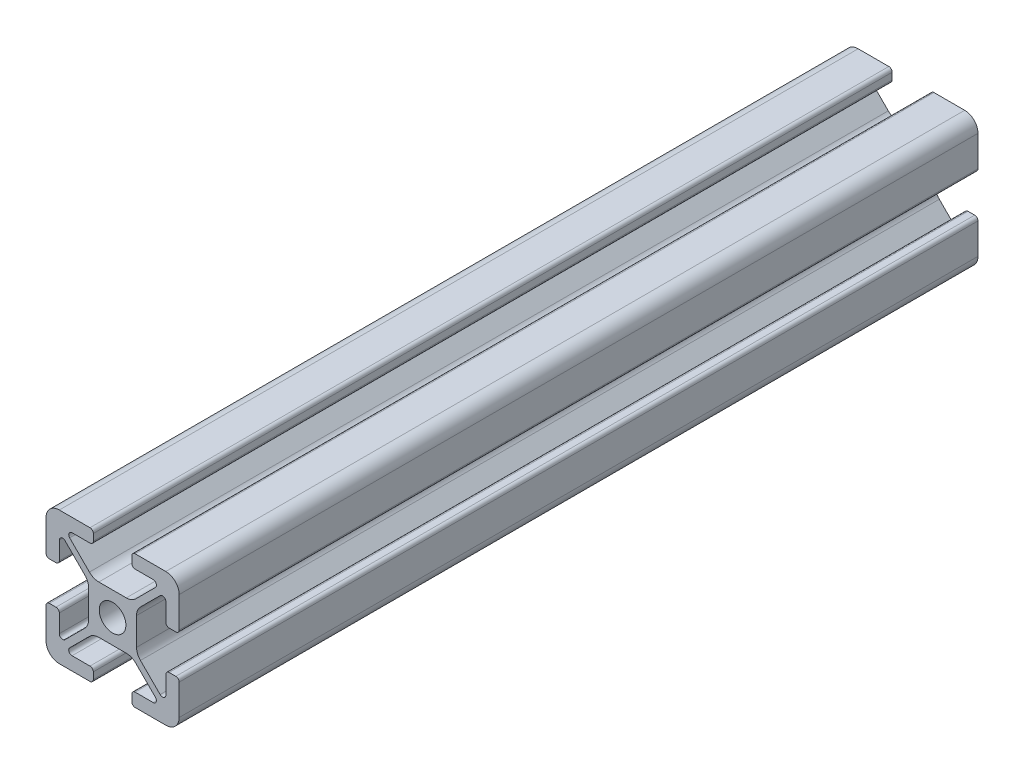
SolidWorks part; units mm, degrees
ref_plane "Front Plane" through (0, 0, 0) normal (0, 0, 1) x (1, 0, 0)
ref_plane "Top Plane" through (0, 0, 0) normal (0, 1, 0) x (1, 0, 0)
ref_plane "Right Plane" through (0, 0, 0) normal (1, 0, 0) x (0, 0, -1)
sketch "Sketch1" plane through (0, 0, 0) normal (0, 0, 1) x (1, 0, 0)
  line L0 (4.4179, 5.3159) -> (8.178, 9.076)
  line L1 (-10.16, -12.7) -> (-4.309, -12.7)
  line L2 (-12.7, -10.16) -> (-12.7, -4.309)
  line L3 (-10.16, 12.7) -> (-4.309, 12.7)
  line L4 (12.7, -10.16) -> (12.7, -4.309)
  line L5 (-12.7, -12.7) -> (12.7, 12.7) construction
  line L6 (-12.7, 12.7) -> (12.7, -12.7) construction
  line L7 (-2.6219, -4.572) -> (2.6219, -4.572)
  line L8 (-4.572, -2.6219) -> (-4.572, 2.6219)
  line L9 (-2.6219, 4.572) -> (2.6219, 4.572)
  line L10 (4.572, -2.6219) -> (4.572, 2.6219)
  line L11 (-4.572, -4.572) -> (4.572, 4.572) construction
  line L12 (-4.572, 4.572) -> (4.572, -4.572) construction
  line L13 (5.3159, 4.4179) -> (9.076, 8.178)
  line L14 (5.3159, -4.4179) -> (9.076, -8.178)
  line L15 (4.4179, -5.3159) -> (8.178, -9.076)
  line L16 (-4.4179, -5.3159) -> (-8.178, -9.076)
  line L17 (-5.3159, -4.4179) -> (-9.076, -8.178)
  line L18 (-5.3159, 4.4179) -> (-9.076, 8.178)
  line L19 (-4.4179, 5.3159) -> (-8.178, 9.076)
  line L20 (-3.674, 4.572) -> (-3.8683, 4.7663) construction
  line L21 (-10.16, 10.16) -> (10.16, 10.16) construction
  line L22 (-7.7289, 10.16) -> (-4.309, 10.16)
  line L23 (10.16, -7.7289) -> (10.16, -4.309)
  line L24 (-7.7289, -10.16) -> (-4.309, -10.16)
  line L25 (-10.16, -7.7289) -> (-10.16, -4.309)
  line L26 (-10.16, -10.16) -> (-10.16, 10.16) construction
  line L27 (-10.16, -10.16) -> (10.16, -10.16) construction
  line L28 (10.16, -10.16) -> (10.16, 10.16) construction
  line L29 (-4.572, 3.674) -> (-17.3082, 3.674) construction
  line L30 (-4.572, -3.674) -> (-17.7261, -3.674) construction
  line L31 (-17.7261, -3.674) -> (20.6347, -3.674) construction
  line L32 (-4.572, 3.674) -> (19.3811, 3.674) construction
  line L33 (-12.7, 4.309) -> (-12.7, 10.16)
  line L34 (-10.16, 4.309) -> (-10.16, 7.7289)
  line L35 (-12.7, -12.7) -> (-12.7, 12.7) construction
  line L36 (12.7, 4.309) -> (12.7, 10.16)
  line L37 (10.16, 4.309) -> (10.16, 7.7289)
  line L38 (12.7, -12.7) -> (12.7, 12.7) construction
  line L39 (-3.674, 10.795) -> (-3.674, 12.065)
  line L40 (3.674, 10.795) -> (3.674, 12.065)
  line L41 (-3.674, -10.795) -> (-3.674, -12.065)
  line L42 (3.674, -10.795) -> (3.674, -12.065)
  line L43 (4.309, -10.16) -> (7.7289, -10.16)
  line L44 (4.309, -12.7) -> (10.16, -12.7)
  line L45 (4.309, 12.7) -> (10.16, 12.7)
  line L46 (-12.7, -12.7) -> (12.7, -12.7) construction
  line L47 (4.309, 10.16) -> (7.7289, 10.16)
  line L48 (-12.7, 12.7) -> (12.7, 12.7) construction
  line L49 (-12.065, 3.674) -> (-10.795, 3.674)
  line L50 (-12.065, -3.674) -> (-10.795, -3.674)
  line L51 (10.795, -3.674) -> (12.065, -3.674)
  line L52 (12.065, 3.674) -> (10.795, 3.674)
  circle A0 centre (0, 0) radius 2.54
  arc A1 (5.3159, -4.4179) -> (4.572, -2.6219) centre (7.112, -2.6219) cw
  arc A2 (5.3159, 4.4179) -> (4.572, 2.6219) centre (7.112, 2.6219) ccw
  arc A3 (4.4179, 5.3159) -> (2.6219, 4.572) centre (2.6219, 7.112) cw
  arc A4 (-4.4179, 5.3159) -> (-2.6219, 4.572) centre (-2.6219, 7.112) ccw
  arc A5 (-5.3159, 4.4179) -> (-4.572, 2.6219) centre (-7.112, 2.6219) cw
  arc A6 (-5.3159, -4.4179) -> (-4.572, -2.6219) centre (-7.112, -2.6219) ccw
  arc A7 (4.4179, -5.3159) -> (2.6219, -4.572) centre (2.6219, -7.112) ccw
  arc A8 (-4.4179, -5.3159) -> (-2.6219, -4.572) centre (-2.6219, -7.112) cw
  arc A9 (-10.16, -12.7) -> (-12.7, -10.16) centre (-10.16, -10.16) cw
  arc A10 (10.16, -12.7) -> (12.7, -10.16) centre (10.16, -10.16) ccw
  arc A11 (10.16, 12.7) -> (12.7, 10.16) centre (10.16, 10.16) cw
  arc A12 (-12.7, 10.16) -> (-10.16, 12.7) centre (-10.16, 10.16) cw
  arc A13 (-7.7289, -10.16) -> (-8.178, -9.076) centre (-7.7289, -9.525) cw
  arc A14 (-10.16, -7.7289) -> (-9.076, -8.178) centre (-9.525, -7.7289) ccw
  arc A15 (10.16, -7.7289) -> (9.076, -8.178) centre (9.525, -7.7289) cw
  arc A16 (8.178, -9.076) -> (7.7289, -10.16) centre (7.7289, -9.525) cw
  arc A17 (9.076, 8.178) -> (10.16, 7.7289) centre (9.525, 7.7289) cw
  arc A18 (8.178, 9.076) -> (7.7289, 10.16) centre (7.7289, 9.525) ccw
  arc A19 (-7.7289, 10.16) -> (-8.178, 9.076) centre (-7.7289, 9.525) ccw
  arc A20 (-9.076, 8.178) -> (-10.16, 7.7289) centre (-9.525, 7.7289) ccw
  arc A21 (-10.16, -4.309) -> (-10.795, -3.674) centre (-10.795, -4.309) ccw
  arc A22 (-12.7, -4.309) -> (-12.065, -3.674) centre (-12.065, -4.309) cw
  arc A23 (-3.674, -12.065) -> (-4.309, -12.7) centre (-4.309, -12.065) cw
  arc A24 (-3.674, -10.795) -> (-4.309, -10.16) centre (-4.309, -10.795) ccw
  arc A25 (3.674, -10.795) -> (4.309, -10.16) centre (4.309, -10.795) cw
  arc A26 (3.674, -12.065) -> (4.309, -12.7) centre (4.309, -12.065) ccw
  arc A27 (10.16, -4.309) -> (10.795, -3.674) centre (10.795, -4.309) cw
  arc A28 (12.7, -4.309) -> (12.065, -3.674) centre (12.065, -4.309) ccw
  arc A29 (10.16, 4.309) -> (10.795, 3.674) centre (10.795, 4.309) ccw
  arc A30 (12.7, 4.309) -> (12.065, 3.674) centre (12.065, 4.309) cw
  arc A31 (4.309, 10.16) -> (3.674, 10.795) centre (4.309, 10.795) cw
  arc A32 (3.674, 12.065) -> (4.309, 12.7) centre (4.309, 12.065) cw
  arc A33 (-4.309, 10.16) -> (-3.674, 10.795) centre (-4.309, 10.795) ccw
  arc A34 (-3.674, 12.065) -> (-4.309, 12.7) centre (-4.309, 12.065) ccw
  arc A35 (-12.7, 4.309) -> (-12.065, 3.674) centre (-12.065, 4.309) ccw
  arc A36 (-10.16, 4.309) -> (-10.795, 3.674) centre (-10.795, 4.309) cw
  point P0 (0, 0)
  point P16 (1.8779, 6.3681)
  point P17 (12.7565, 17.2467)
  point P18 (2.7759, 5.47)
  point P20 (4.572, -3.674)
  point P28 (4.572, 3.674)
  point P31 (0, 0)
  point P32 (13.6546, 16.3486)
  point P66 (3.674, 4.572)
  point P110 (-10.16, -3.674)
  point P113 (-12.7, -3.674)
  point P120 (3.674, -10.16)
  point P123 (3.674, -12.7)
  point P126 (10.16, -3.674)
  point P129 (12.7, -3.674)
  point P132 (10.16, 3.674)
  point P135 (12.7, 3.674)
  point P140 (3.674, 12.7)
  point P147 (-12.7, 3.674)
  point P150 (-10.16, 3.674)
  dimension "D3" = 5.08
  dimension "D8" = 2.54
  dimension "D9" = 0.635
  dimension "D10" = 0.635
  dimension "D1" = 25.4
  dimension "D2" = 25.4
  dimension "D4" = 9.144
  dimension "D5" = 1.27
  dimension "D7" = 2.54
  dimension "D6" = 4
extrude "Boss-Extrude1" add sketch "Sketch1" along normal blind 152.4
